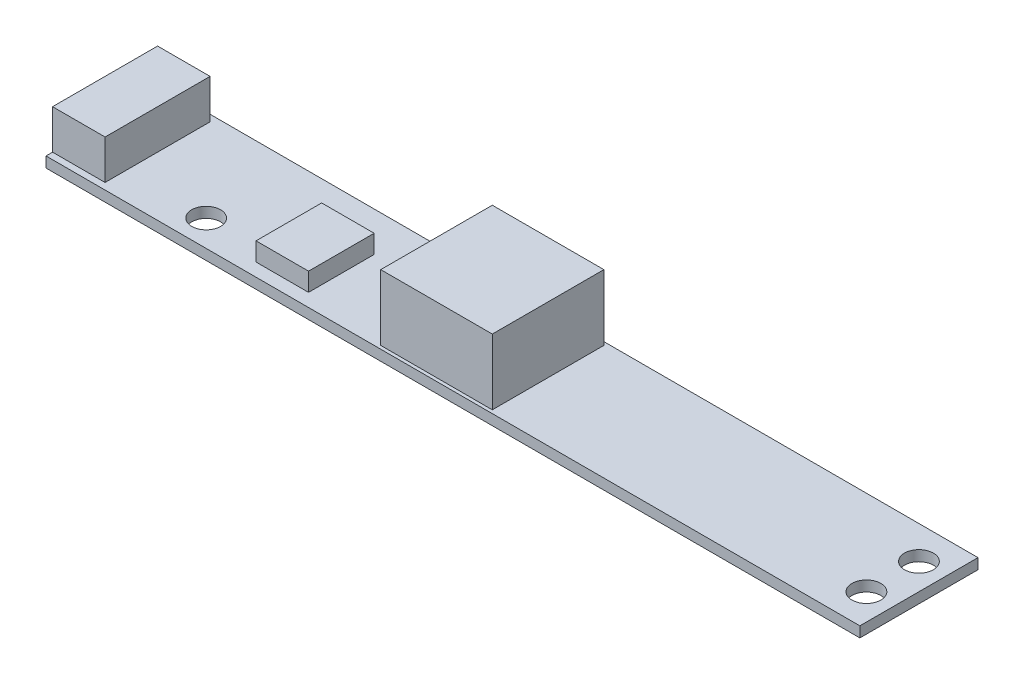
SolidWorks part; units mm, degrees
material "A-玻璃纤维"
ref_plane "前视基准面" through (0, 0, 0) normal (0, 0, 1) x (1, 0, 0)
ref_plane "上视基准面" through (0, 0, 0) normal (0, 1, 0) x (1, 0, 0)
ref_plane "右视基准面" through (0, 0, 0) normal (1, 0, 0) x (0, 0, -1)
other "Configuration Table"
sketch "草图1" plane through (0, 0, 0) normal (0, 1, 0) x (1, 0, 0)
  line L0 (0, 0) -> (0, 25.5191) construction
  line L1 (-31, -4.5) -> (31, -4.5)
  line L2 (-31, -4.5) -> (-31, 4.5)
  line L3 (-31, 4.5) -> (31, 4.5)
  line L4 (31, -4.5) -> (31, 4.5)
  line L5 (-31, -4.5) -> (31, 4.5) construction
  line L6 (-31, 4.5) -> (31, -4.5) construction
  line L7 (0, 0) -> (36.7583, 0) construction
  line L8 (-1.5, 0) -> (-1.5, 16.0166) construction
  circle A0 centre (29, 2) radius 1.1
  circle A1 centre (29, -2) radius 1.1
  circle A2 centre (-20.8, -2.5) radius 1.1
  point P0 (0, 0)
  dimension "D3" = 2.2
  dimension "D4" = 4
  dimension "D5" = 2
  dimension "D7" = 2.2
  dimension "D8" = 2
  dimension "D9" = 10.2
  dimension "D1" = 62
  dimension "D2" = 32.5
  dimension "D6" = 9
extrude "凸台-拉伸1" add sketch "草图1" along normal blind 0.8
sketch "草图3" plane through (0, 0.8, 0) normal (0, 1, 0) x (1, 0, 0)
  line L1 (-5.75, -4.25) -> (2.75, -4.25)
  line L2 (-5.75, -4.25) -> (-5.75, 4.25)
  line L3 (-5.75, 4.25) -> (2.75, 4.25)
  line L4 (2.75, -4.25) -> (2.75, 4.25)
  line L5 (-5.75, -4.25) -> (2.75, 4.25) construction
  line L6 (-5.75, 4.25) -> (2.75, -4.25) construction
  point P0 (-1.5, 0)
  dimension "D1" = 8.5
  dimension "D2" = 8.5
extrude "凸台-拉伸2" add sketch "草图3" along normal blind 5
sketch "草图4" plane through (0, 0.8, 0) normal (0, 1, 0) x (1, 0, 0)
  line L0 (-31, 0) -> (-31, 4)
  line L1 (-31, -4.5) -> (-31, 4.5) construction
  line L2 (-31, 4) -> (-27, 4)
  line L3 (-27, 4) -> (-27, -1.2222)
  line L4 (-27, -1.2222) -> (-27, -4)
  line L5 (-27, -4) -> (-31, -4)
  line L6 (-31, -4) -> (-31, 0)
  dimension "D1" = 4
  dimension "D2" = 4
  dimension "D3" = 4
extrude "凸台-拉伸3" add sketch "草图4" along normal blind 3
sketch "草图5" plane through (0, 0.8, 0) normal (0, 1, 0) x (1, 0, 0)
  line L1 (-16, -3.5) -> (-12, -3.5)
  line L2 (-16, -3.5) -> (-16, 1.5)
  line L3 (-16, 1.5) -> (-12, 1.5)
  line L4 (-12, -3.5) -> (-12, 1.5)
  line L5 (-16, -3.5) -> (-12, 1.5) construction
  line L6 (-16, 1.5) -> (-12, -3.5) construction
  point P0 (-14, -1)
  dimension "D1" = 4
  dimension "D2" = 5
  dimension "D3" = 14
  dimension "D4" = 1
extrude "凸台-拉伸4" add sketch "草图5" along normal blind 1.4
